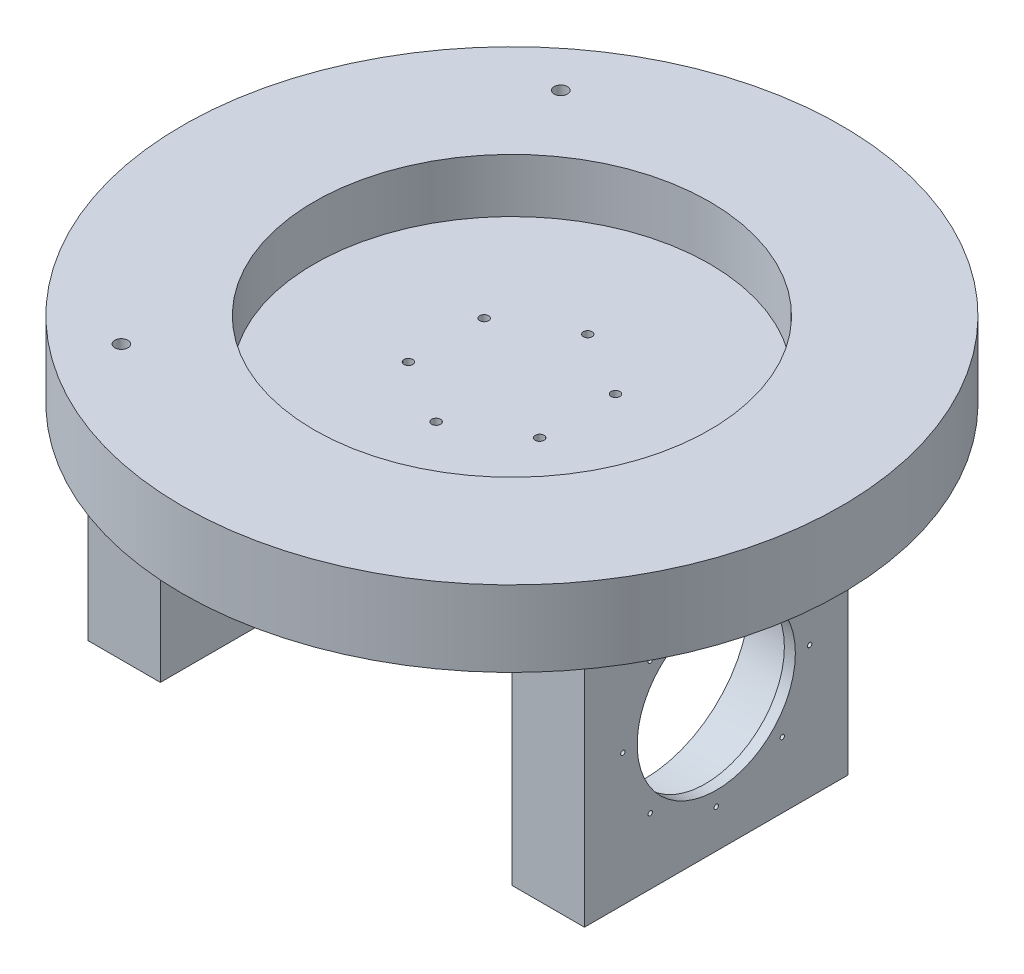
SolidWorks part; units mm, degrees
ref_plane "前视基准面" through (0, 0, 0) normal (0, 0, 1) x (1, 0, 0)
ref_plane "上视基准面" through (0, 0, 0) normal (0, 1, 0) x (1, 0, 0)
ref_plane "右视基准面" through (0, 0, 0) normal (1, 0, 0) x (0, 0, -1)
other "Configuration Table"
sketch "草图1" plane through (0, 0, 0) normal (0, 1, 0) x (1, 0, 0)
  circle A0 centre (0, 0) radius 150
extrude "凸台-拉伸1" add sketch "草图1" along normal blind 34.5
sketch "草图2" plane through (0, 0, 0) normal (0, -1, 0) x (-1, 0, 0)
  line L0 (0, 0) -> (67.76, 0) construction
  line L1 (0, 0) -> (-60, 0)
  line L2 (100, 0) -> (100, 60)
  line L3 (100, 0) -> (100, -60)
  line L4 (-60, 0) -> (-60, 60)
  line L5 (-60, 0) -> (-60, -60)
  line L6 (100, 60) -> (133, 60)
  line L7 (100, -60) -> (133, -60)
  line L8 (133, 60) -> (133, -60)
  line L9 (-60, 60) -> (-93, 60)
  line L10 (-93, 60) -> (-93, -60)
  line L11 (-93, -60) -> (-60, -60)
  line L12 (67.76, 60) -> (67.76, -60) construction
  line L13 (67.76, -60) -> (77.76, -60) construction
  line L19 (77.76, -60) -> (77.76, 60) construction
  line L20 (77.76, 60) -> (67.76, 60) construction
  dimension "D1" = 33
  dimension "D2" = 60
  dimension "D3" = 100
  dimension "D4" = 33
  dimension "D5" = 120
  dimension "D6" = 60
  dimension "D7" = 120
  dimension "D8" = 60
extrude "凸台-拉伸2" add sketch "草图2" along normal blind 130 contours L10 L11 L5 L4 L9 | L8 L6 L2 L3 L7 | L13 L19 L20 L12
sketch "草图3" plane through (93, 0, 0) normal (1, 0, 0) x (0, 0, -1)
  circle A0 centre (0, -70) radius 48.25
extrude "切除-拉伸1" cut sketch "草图3" against normal through all
sketch "草图4" plane through (0, 34.5, 0) normal (0, 1, 0) x (1, 0, 0)
  circle A0 centre (0, 0) radius 90
extrude "切除-拉伸2" cut sketch "草图4" against normal blind 24.5 contours A0
sketch "草图6" plane through (93, 0, 0) normal (1, 0, 0) x (0, 0, -1)
  circle A0 centre (0, -70) radius 48.25
extrude "凸台-拉伸3" add sketch "草图6" against normal blind 5
pattern_linear "阵列(线性)1" count 2 spacing 221 along (-1, 0, 0) of "凸台-拉伸3"
sketch "草图10" plane through (93, 0, 0) normal (1, 0, 0) x (0, 0, -1)
  circle A1 centre (0, -70) radius 32
extrude "切除-拉伸3" cut sketch "草图10" against normal blind 5
sketch "草图11" plane through (93, 0, 0) normal (1, 0, 0) x (0, 0, -1)
  circle A1 centre (0, -27.5) radius 1
extrude "切除-拉伸4" cut sketch "草图11" against normal blind 5
pattern_circular "阵列(圆周)1" count 8 over 360 about axis through (0, -70, 0) along (1, 0, 0) of "切除-拉伸4"
pattern_linear "阵列(线性)3" count 2 spacing 221 along (-1, 0, 0) of "阵列(圆周)1", "切除-拉伸4"
pattern_linear "阵列(线性)4" count 2 spacing 221 along (-1, 0, 0) of "切除-拉伸3"
sketch "草图14" plane through (0, 0, 0) normal (0, -1, 0) x (1, 0, 0)
  circle A0 centre (-77.76, -100) radius 3
extrude "切除-拉伸5" cut sketch "草图14" against normal through all
mirror "镜向1" about plane through (0, 0, 0) normal (0, 0, 1) of "切除-拉伸5"
sketch "草图16" plane through (0, 10, 0) normal (0, 1, 0) x (1, 0, 0)
  arc A0 (1.9992, 34.442) -> (-1.9992, 34.442) centre (0, 0) ccw
  circle A1 centre (0, 34.5) radius 2
extrude "切除-拉伸6" cut sketch "草图16" against normal through all contours A1
pattern_circular "阵列(圆周)2" count 6 over 360 about axis through (0, 0, 0) along (0, 1, 0) of "切除-拉伸6"
sketch "草图17" plane through (93, 0, 0) normal (1, 0, 0) x (0, 0, -1)
  circle A0 centre (0, -70) radius 36
extrude "切除-拉伸7" cut sketch "草图17" against normal blind 10
